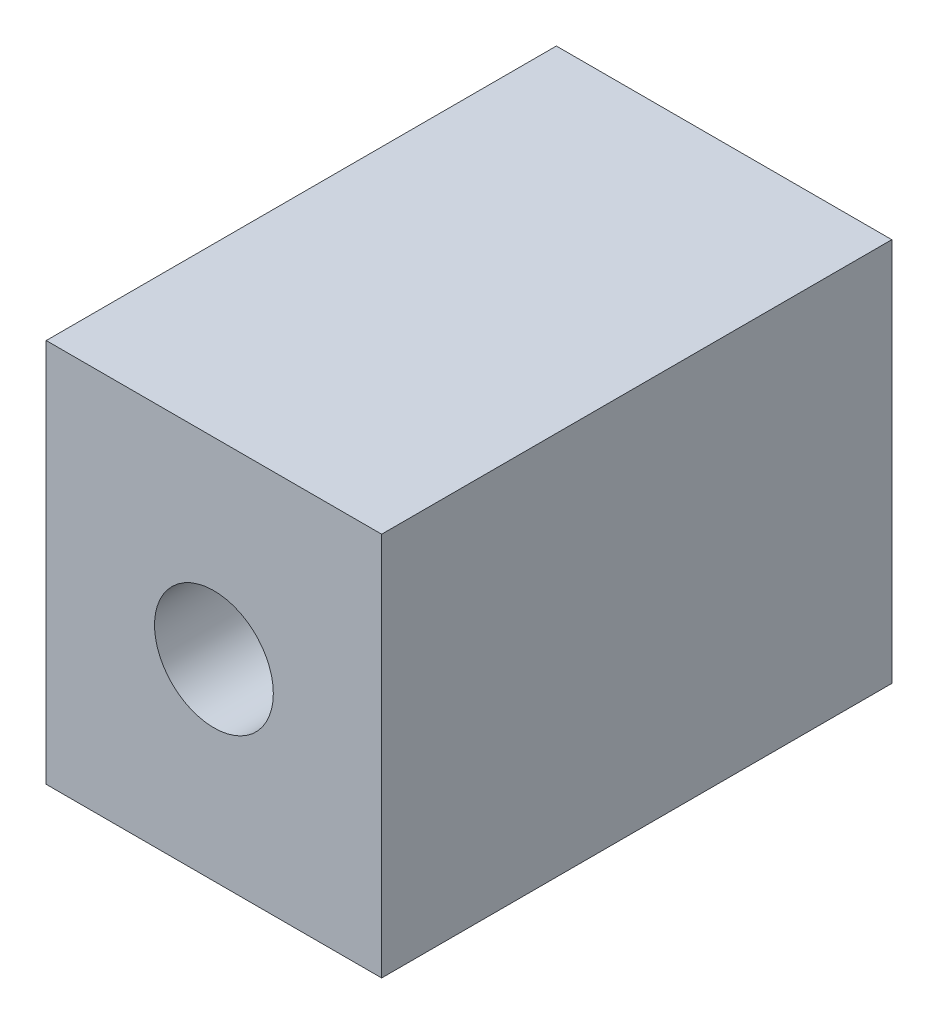
SolidWorks part; units mm, degrees
ref_plane "前视基准面" through (0, 0, 0) normal (0, 0, 1) x (1, 0, 0)
ref_plane "上视基准面" through (0, 0, 0) normal (0, 1, 0) x (1, 0, 0)
ref_plane "右视基准面" through (0, 0, 0) normal (1, 0, 0) x (0, 0, -1)
sketch "草图1" plane through (0, 0, 0) normal (0, 0, 1) x (1, 0, 0)
  line L0 (0, 27.5) -> (0, -27.5) construction
  line L1 (24, -27.5) -> (-24, -27.5)
  line L2 (24, -27.5) -> (24, 27.5)
  line L3 (24, 27.5) -> (-24, 27.5)
  line L4 (-24, -27.5) -> (-24, 27.5)
  line L5 (24, -27.5) -> (-24, 27.5) construction
  line L6 (24, 27.5) -> (-24, -27.5) construction
  circle A0 centre (0, 0) radius 8.5
  point P0 (0, 0)
  dimension "D3" = 17
  dimension "D4" = 27.5
  dimension "D1" = 55
  dimension "D2" = 48
extrude "凸台-拉伸1" add sketch "草图1" along normal blind 73
scale "缩放比例1" scale about origin uniform scaling yes scale factor 0.3
